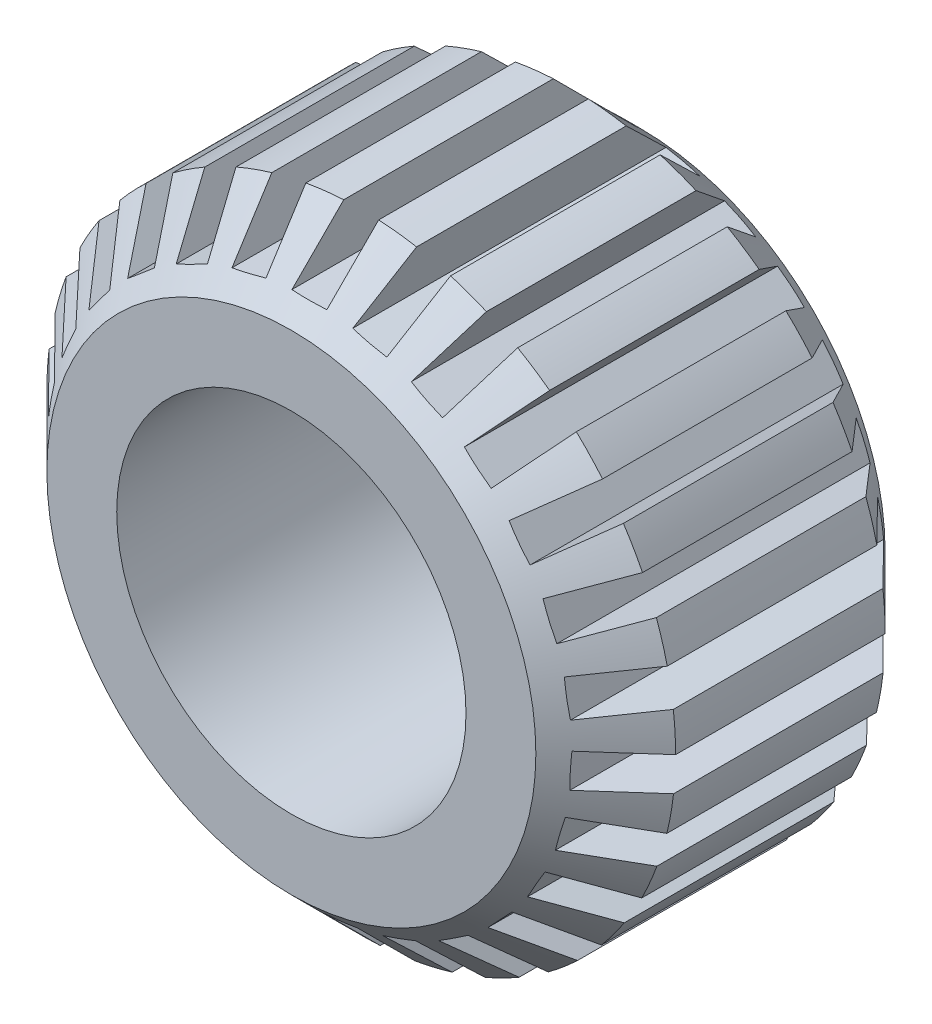
SolidWorks part; units mm, degrees
ref_plane "Front Plane" through (0, 0, 0) normal (0, 0, 1) x (1, 0, 0)
ref_plane "Top Plane" through (0, 0, 0) normal (0, 1, 0) x (1, 0, 0)
ref_plane "Right Plane" through (0, 0, 0) normal (1, 0, 0) x (0, 0, -1)
sketch "Sketch2" plane through (0, 0, 0) normal (0, 0, 1) x (1, 0, 0)
  circle A0 centre (0, 0) radius 5
  circle A1 centre (0, 0) radius 9
  dimension "D1" = 10
  dimension "D2" = 4
extrude "Boss-Extrude1" add sketch "Sketch2" along normal blind 10
chamfer "Chamfer1" distance 2 angle 45 2 edges at (9, 0, 0) (9, 0, 10)
sketch "Sketch3" plane through (0, 0, 0) normal (0, 0, 1) x (1, 0, 0)
  line L0 (0, 0) -> (0, 9) construction
  line L1 (0.5, 7.5) -> (0.5, 8.9861)
  line L2 (-0.5, 7.5) -> (-0.5, 8.9861)
  line L3 (-0.5, 7.5) -> (0.5, 7.5)
  line L5 (0.5, 0) -> (0.5, 9) construction
  line L6 (-0.5, 0) -> (-0.5, 9) construction
  circle A0 centre (0, 0) radius 9 construction
  arc A1 (0.5, 8.9861) -> (-0.5, 8.9861) centre (0, 0) ccw
  point P10 (0, 0)
  dimension "D3" = 7.5
  dimension "D1" = 0.5
  dimension "D2" = 0.5
extrude "Cut-Extrude1" cut sketch "Sketch3" along normal through all
pattern_circular "CirPattern1" count 27 over 360 about axis through (0, 0, 0) along (0, 0, 1) of "Cut-Extrude1"
